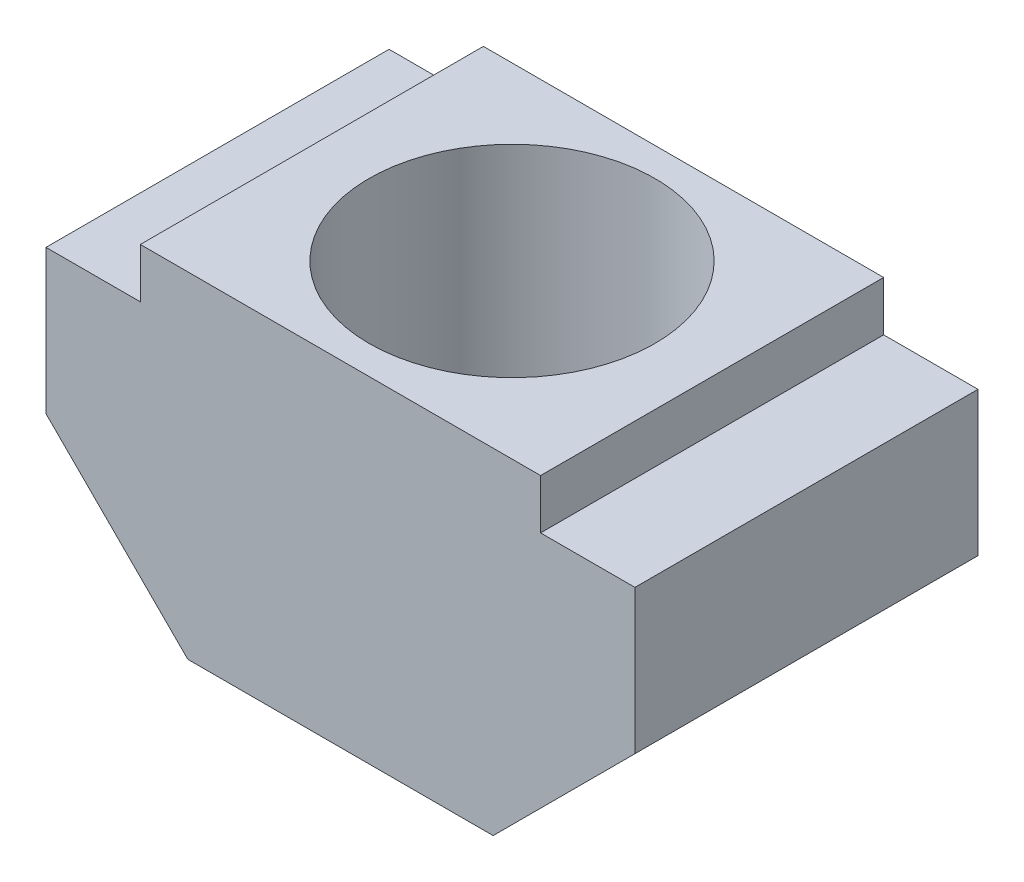
SolidWorks part; units mm, degrees
material "Plain Carbon Steel"
ref_plane "Front Plane" through (0, 0, 0) normal (0, 0, 1) x (1, 0, 0)
ref_plane "Top Plane" through (0, 0, 0) normal (0, 1, 0) x (1, 0, 0)
ref_plane "Right Plane" through (0, 0, 0) normal (1, 0, 0) x (0, 0, -1)
sketch "Sketch1" plane through (0, 0, 0) normal (0, 0, 1) x (1, 0, 0)
  line L0 (2.6699, 0) -> (-2.6699, 0)
  line L1 (-2.6699, 0) -> (-5.15, 2.4801)
  line L2 (-5.15, 2.4801) -> (-5.15, 5)
  line L3 (-5.15, 5) -> (-3.5, 5)
  line L4 (-3.5, 5) -> (-3.5, 5.869)
  line L5 (-3.5, 5.869) -> (3.5, 5.869)
  line L6 (0, 5.869) -> (0, 0) construction
  line L7 (3.5, 5) -> (3.5, 5.869)
  line L8 (5.15, 5) -> (3.5, 5)
  line L9 (5.15, 2.4801) -> (5.15, 5)
  line L10 (2.6699, 0) -> (5.15, 2.4801)
  dimension "D1" = 10.3
  dimension "D2" = 5
  dimension "D3" = 45
  dimension "D4" = 7
extrude "Boss-Extrude1" add sketch "Sketch1" along normal blind 6
sketch "Sketch2" plane through (0, 5.869, 0) normal (0, 1, 0) x (1, 0, 0)
  line L0 (-3.5, -6) -> (-3.5, 0) construction
  line L1 (3.5, -6) -> (-3.5, -6) construction
  circle A0 centre (0, -3) radius 2.5
  point P2 (-3.5, -3)
  point P3 (0, -6)
  dimension "D1" = 5
extrude "Cut-Extrude1" cut sketch "Sketch2" against normal through all
